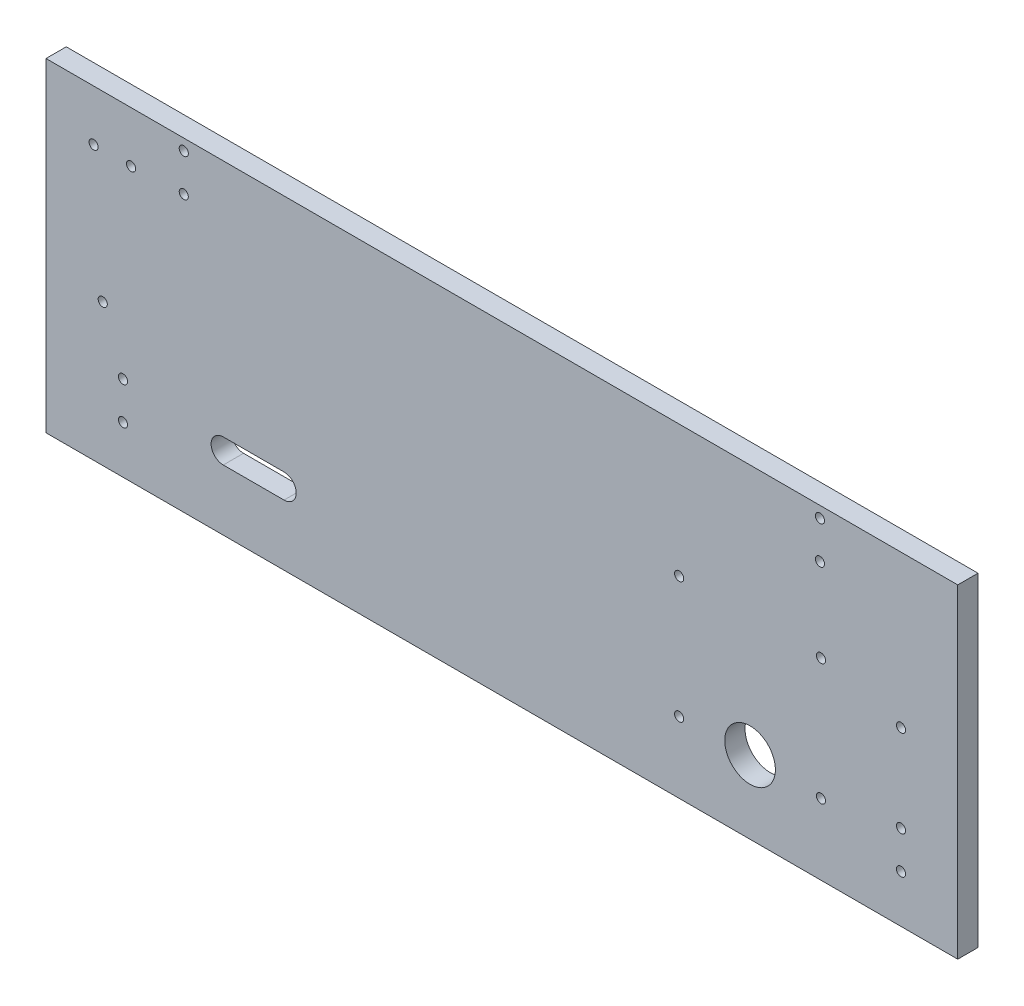
SolidWorks part; units mm, degrees
material "Multistrato di pioppo"
ref_plane "Piano frontale" through (0, 0, 0) normal (0, 0, 1) x (1, 0, 0)
ref_plane "Piano superiore" through (0, 0, 0) normal (0, 1, 0) x (1, 0, 0)
ref_plane "Piano destro" through (0, 0, 0) normal (1, 0, 0) x (0, 0, -1)
sketch "Schizzo1" plane through (0, 0, 0) normal (0, 0, 1) x (1, 0, 0)
  line L1 (0, 0) -> (450, 0)
  line L2 (0, 0) -> (0, 160)
  line L3 (0, 160) -> (450, 160)
  line L4 (450, 0) -> (450, 160)
  dimension "D1" = 450
  dimension "D2" = 160
extrude "Estrusione-Estrusione1" add sketch "Schizzo1" along normal blind 10
sketch "Schizzo2" plane through (0, 0, 10) normal (0, 0, 1) x (1, 0, 0)
  line L0 (102.5, 36) -> (347.5, 36) construction
  line L1 (225, 0) -> (225, 36) construction
  line L2 (0, 0) -> (450, 0) construction
  line L3 (87.5, 36) -> (117.5, 36) construction
  line L4 (87.5, 42) -> (117.5, 42)
  line L5 (87.5, 30) -> (117.5, 30)
  circle A1 centre (347.5, 36) radius 12.5
  arc A2 (87.5, 42) -> (87.5, 30) centre (87.5, 36) ccw
  arc A3 (117.5, 30) -> (117.5, 42) centre (117.5, 36) ccw
  circle A8 centre (382, 154.5) radius 2.25
  circle A9 centre (382, 136) radius 2.25
  circle A10 centre (68, 154.5) radius 2.25
  circle A11 centre (68, 136) radius 2.25
  circle A12 centre (38, 42) radius 2.25
  circle A13 centre (38, 23.5) radius 2.25
  circle A14 centre (422, 23.5) radius 2.25
  circle A15 centre (422, 42) radius 2.25
  circle A16 centre (23.5, 134.9337) radius 2.25
  circle A17 centre (42, 134.9337) radius 2.25
  circle A18 centre (28, 70) radius 2.25
  circle A19 centre (422, 85) radius 2.25
  circle A20 centre (312.5, 95) radius 2.25
  circle A21 centre (382.5, 95) radius 2.25
  circle A22 centre (382.5, 35) radius 2.25
  circle A23 centre (312.5, 35) radius 2.25
  point P9 (102.5, 36)
  dimension "D2" = 25
  dimension "D3" = 12
  dimension "D5" = 30
  dimension "D6" = 4.5
  dimension "D20" = 4.5
  dimension "D11" = 4.5
  dimension "D1" = 36
  dimension "D4" = 245
extrude "Taglio-Estrusione1" cut sketch "Schizzo2" against normal blind 10
